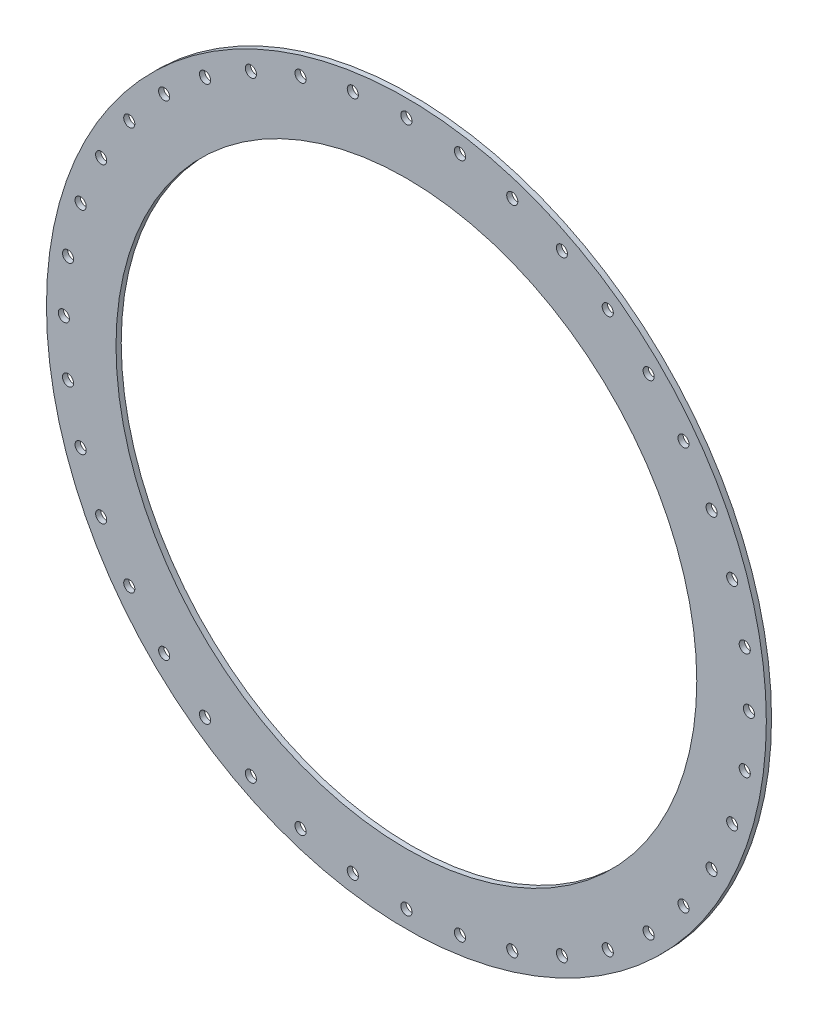
SolidWorks part; units mm, degrees
material "Thornel Mat VMA"
ref_plane "前视基准面" through (0, 0, 0) normal (0, 0, 1) x (1, 0, 0)
ref_plane "上视基准面" through (0, 0, 0) normal (0, 1, 0) x (1, 0, 0)
ref_plane "右视基准面" through (0, 0, 0) normal (1, 0, 0) x (0, 0, -1)
sketch "草图1" plane through (0, 0, 0) normal (0, 0, 1) x (1, 0, 0)
  circle A0 centre (0, 0) radius 98.5 construction
  circle A1 centre (0, 0) radius 103.5
  circle A2 centre (0, 0) radius 83.5
  circle A3 centre (0, 98.5) radius 1.6
  circle A4 centre (15.4088, 97.2873) radius 1.6
  circle A5 centre (30.4382, 93.6791) radius 1.6
  circle A6 centre (44.7181, 87.7641) radius 1.6
  circle A7 centre (57.8968, 79.6882) radius 1.6
  circle A8 centre (69.65, 69.65) radius 1.6
  circle A9 centre (79.6882, 57.8968) radius 1.6
  circle A10 centre (87.7641, 44.7181) radius 1.6
  circle A11 centre (93.6791, 30.4382) radius 1.6
  circle A12 centre (97.2873, 15.4088) radius 1.6
  circle A13 centre (98.5, 0) radius 1.6
  circle A14 centre (97.2873, -15.4088) radius 1.6
  circle A15 centre (93.6791, -30.4382) radius 1.6
  circle A16 centre (87.7641, -44.7181) radius 1.6
  circle A17 centre (79.6882, -57.8968) radius 1.6
  circle A18 centre (69.65, -69.65) radius 1.6
  circle A19 centre (57.8968, -79.6882) radius 1.6
  circle A20 centre (44.7181, -87.7641) radius 1.6
  circle A21 centre (30.4382, -93.6791) radius 1.6
  circle A22 centre (15.4088, -97.2873) radius 1.6
  circle A23 centre (0, -98.5) radius 1.6
  circle A24 centre (-15.4088, -97.2873) radius 1.6
  circle A25 centre (-30.4382, -93.6791) radius 1.6
  circle A26 centre (-44.7181, -87.7641) radius 1.6
  circle A27 centre (-57.8968, -79.6882) radius 1.6
  circle A28 centre (-69.65, -69.65) radius 1.6
  circle A29 centre (-79.6882, -57.8968) radius 1.6
  circle A30 centre (-87.7641, -44.7181) radius 1.6
  circle A31 centre (-93.6791, -30.4382) radius 1.6
  circle A32 centre (-97.2873, -15.4088) radius 1.6
  circle A33 centre (-98.5, 0) radius 1.6
  circle A34 centre (-97.2873, 15.4088) radius 1.6
  circle A35 centre (-93.6791, 30.4382) radius 1.6
  circle A36 centre (-87.7641, 44.7181) radius 1.6
  circle A37 centre (-79.6882, 57.8968) radius 1.6
  circle A38 centre (-69.65, 69.65) radius 1.6
  circle A39 centre (-57.8968, 79.6882) radius 1.6
  circle A40 centre (-44.7181, 87.7641) radius 1.6
  circle A41 centre (-30.4382, 93.6791) radius 1.6
  circle A42 centre (-15.4088, 97.2873) radius 1.6
  point P7 (20.4404, 88.5968)
  point P8 (0, 0)
  point P88 (0, 0)
  dimension "D1" = 207
  dimension "D2" = 197
  dimension "D3" = 167
  dimension "D4" = 3.2
  dimension "D5" = 40
extrude "凸台-拉伸1" add sketch "草图1" along normal blind 1.5
